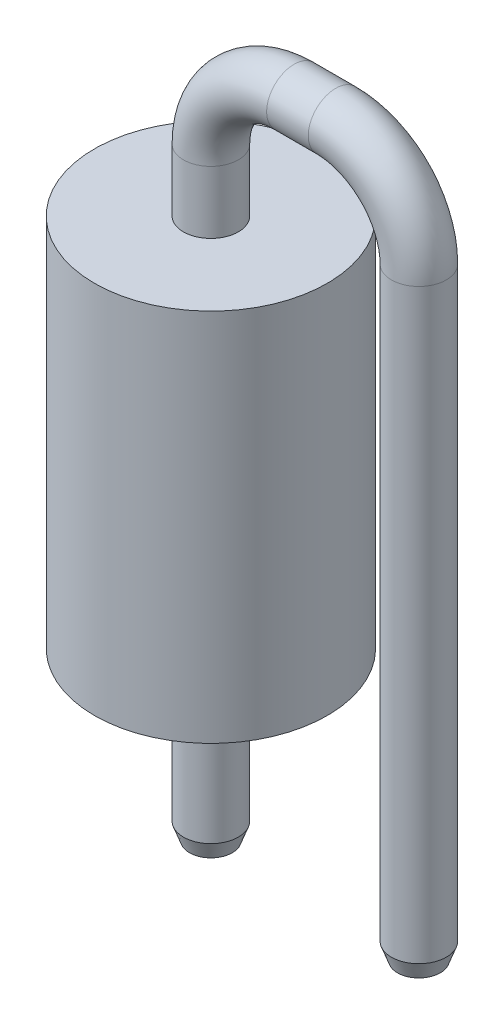
SolidWorks part; units mm, degrees
ref_plane "Спереди" through (0, 0, 0) normal (0, 0, 1) x (1, 0, 0)
ref_plane "Сверху" through (0, 0, 0) normal (0, 1, 0) x (1, 0, 0)
ref_plane "Справа" through (0, 0, 0) normal (1, 0, 0) x (0, 0, -1)
sketch "Эскиз1" plane through (0, 0, 0) normal (0, 1, 0) x (1, 0, 0)
  circle A0 centre (0, 0) radius 0.66
  dimension "D1" = 1.32
sketch "Эскиз2" plane through (0, 0, 0) normal (0, 0, 1) x (1, 0, 0)
  line L0 (0, 0) -> (0, 14.5)
  line L1 (2, 16.5) -> (3, 16.5)
  line L2 (5, 14.5) -> (5, 0)
  arc A0 (5, 14.5) -> (3, 16.5) centre (3, 14.5) ccw
  arc A1 (0, 14.5) -> (2, 16.5) centre (2, 14.5) cw
  dimension "D1" = 2
  dimension "D2" = 16.5
  dimension "D3" = 5
sweep "По траектории1" add profiles "Эскиз1" path "Эскиз2"
sketch "Эскиз3" plane through (0, 0, 0) normal (0, 1, 0) x (1, 0, 0)
  circle A0 centre (0, 0) radius 2.8
  dimension "D1" = 5.6
extrude "Бобышка-Вытянуть1" add sketch "Эскиз3" along normal blind 9 from offset 4
chamfer "Фаска1" distance 0.4 angle 20 2 edges at (5, 0, 0.66) (0, 0, 0.66)
